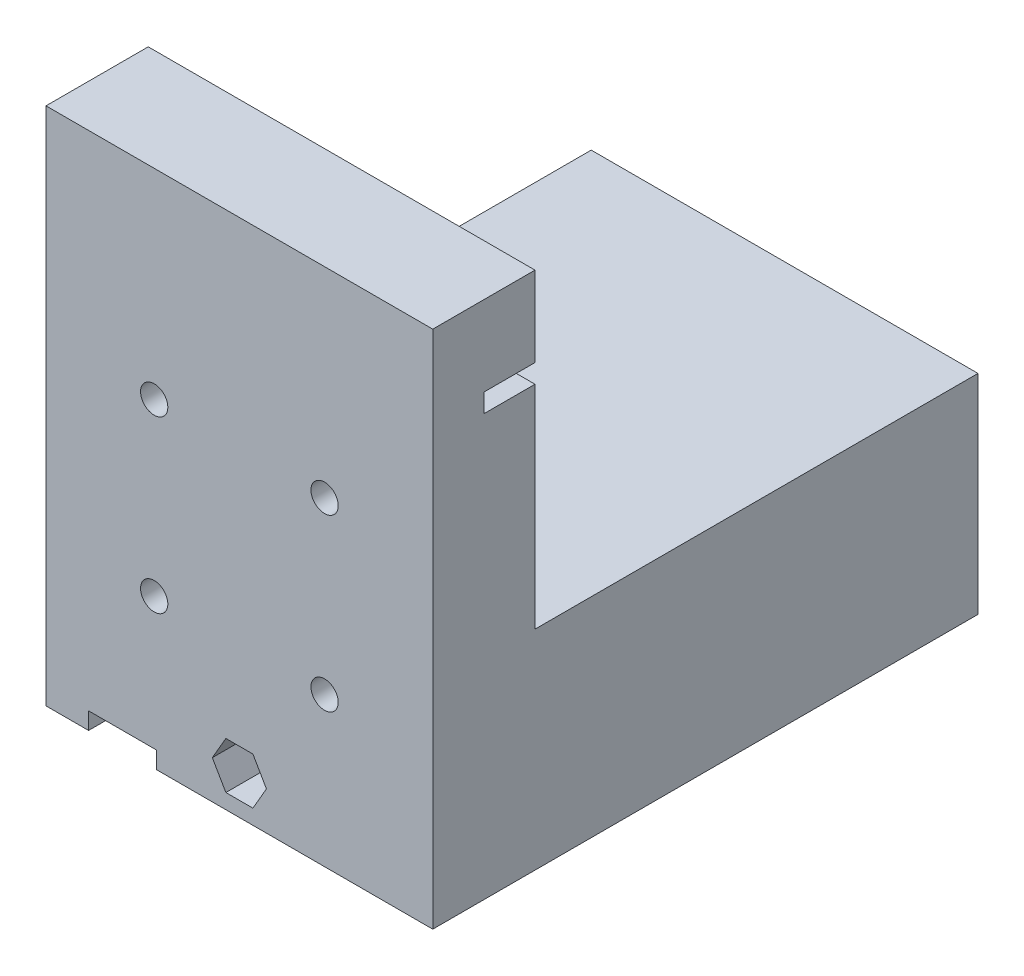
SolidWorks part; units mm, degrees
ref_plane "前视基准面" through (0, 0, 0) normal (0, 0, 1) x (1, 0, 0)
ref_plane "上视基准面" through (0, 0, 0) normal (0, 1, 0) x (1, 0, 0)
ref_plane "右视基准面" through (0, 0, 0) normal (1, 0, 0) x (0, 0, -1)
sketch "草图1" plane through (0, 0, 0) normal (0, 0, 1) x (1, 0, 0)
  line L1 (-54.7963, 27.5425) -> (-9.3963, 27.5425)
  line L2 (-54.7963, 27.5425) -> (-54.7963, 0.5425)
  line L3 (-54.7963, 0.5425) -> (-9.3963, 0.5425)
  line L4 (-9.3963, 27.5425) -> (-9.3963, 0.5425)
  dimension "D1" = 45.4
  dimension "D2" = 27
extrude "凸台-拉伸1" add sketch "草图1" along normal blind 7
sketch "草图2" plane through (0, 0, 0) normal (0, 0, -1) x (-1, 0, 0)
  line L0 (32.0963, 27.5425) -> (32.0963, 0.5425) construction
  line L1 (9.3963, 27.5425) -> (54.7963, 27.5425) construction
  line L2 (54.7963, 0.5425) -> (9.3963, 0.5425) construction
  line L3 (9.3963, 14.0425) -> (54.7963, 14.0425) construction
  line L4 (9.3963, 0.5425) -> (9.3963, 27.5425) construction
  line L5 (54.7963, 27.5425) -> (54.7963, 0.5425) construction
  circle A0 centre (22.0963, 24.0425) radius 1.6
  circle A1 centre (42.0963, 24.0425) radius 1.6
  circle A2 centre (42.0963, 4.0425) radius 1.6
  circle A3 centre (22.0963, 4.0425) radius 1.6
  point P9 (32.0963, 14.0425)
  dimension "D1" = 3.2
  dimension "D2" = 10
  dimension "D3" = 10
extrude "切除-拉伸1" cut sketch "草图2" against normal through all
sketch "草图4" plane through (0, 0, 0) normal (0, 0, -1) x (-1, 0, 0)
  line L0 (38.3463, 0.5425) -> (54.7963, 0.5425)
  line L1 (25.8463, 0.5425) -> (38.3463, 0.5425)
  line L8 (32.0963, 27.5425) -> (32.0963, 0.5425) construction
  line L9 (9.3963, 14.0425) -> (54.7963, 14.0425) construction
  line L11 (9.3963, 27.5425) -> (54.7963, 27.5425)
  line L12 (9.3963, 27.5425) -> (9.3963, 0.5425)
  line L13 (9.3963, 0.5425) -> (25.8463, 0.5425)
  line L14 (54.7963, 27.5425) -> (54.7963, 0.5425)
  circle A8 centre (42.0963, 24.0425) radius 3.1
  circle A9 centre (22.0963, 24.0425) radius 3.1
  circle A10 centre (22.0963, 24.0425) radius 3.1
  circle A11 centre (42.0963, 4.0425) radius 3.1
  circle A12 centre (22.0963, 4.0425) radius 3.1
  dimension "D1" = 1.5
extrude "凸台-拉伸2" add sketch "草图4" along normal blind 5
sketch "草图5" plane through (0, 27.5425, 0) normal (0, 1, 0) x (1, 0, 0)
  line L1 (-54.7963, 5) -> (-9.3963, 5)
  line L2 (-54.7963, 5) -> (-54.7963, -7)
  line L3 (-54.7963, -7) -> (-9.3963, -7)
  line L4 (-9.3963, 5) -> (-9.3963, -7)
extrude "凸台-拉伸3" add sketch "草图5" along normal blind 20 contours L2 L3 L4 L1
sketch "草图7" plane through (0, 0, -5) normal (0, 0, -1) x (-1, 0, 0)
  line L0 (9.3963, 27.5425) -> (54.7963, 27.5425) construction
  line L1 (9.3963, 47.5425) -> (9.3963, 0.5425) construction
  line L2 (54.7963, 0.5425) -> (54.7963, 47.5425) construction
  line L3 (9.3963, 0.5425) -> (54.7963, 0.5425) construction
  line L4 (9.3963, 37.0425) -> (54.7963, 37.0425) construction
  line L5 (32.0963, 47.5425) -> (32.0963, 27.5425) construction
  line L6 (54.7963, 47.5425) -> (9.3963, 47.5425) construction
  line L7 (9.3963, 38.1425) -> (16.3755, 38.1425)
  line L8 (9.3963, 35.9425) -> (16.3755, 35.9425)
  line L9 (9.3963, 38.1425) -> (9.3963, 35.9425)
  line L10 (54.7963, 35.9425) -> (47.8172, 35.9425)
  line L11 (54.7963, 38.1425) -> (47.8172, 38.1425)
  line L12 (54.7963, 38.1425) -> (54.7963, 35.9425)
  circle A0 centre (25.4963, 37.0425) radius 5
  circle A1 centre (38.6963, 37.0425) radius 5
  arc A2 (31.2713, 40.9984) -> (19.1117, 39.9125) centre (25.4963, 37.0425) ccw
  arc A3 (32.9213, 40.9984) -> (45.0809, 39.9125) centre (38.6963, 37.0425) cw
  arc A4 (19.1117, 34.1725) -> (31.2713, 33.0866) centre (25.4963, 37.0425) ccw
  circle A5 centre (38.6963, 37.0425) radius 7 construction
  circle A6 centre (25.4963, 37.0425) radius 7 construction
  arc A7 (45.0809, 34.1725) -> (32.9213, 33.0866) centre (38.6963, 37.0425) cw
  arc A8 (47.8172, 35.9425) -> (45.0809, 34.1725) centre (47.8172, 32.9425) ccw
  arc A9 (47.8172, 38.1425) -> (45.0809, 39.9125) centre (47.8172, 41.1425) cw
  arc A10 (16.3755, 35.9425) -> (19.1117, 34.1725) centre (16.3755, 32.9425) cw
  arc A11 (16.3755, 38.1425) -> (19.1117, 39.9125) centre (16.3755, 41.1425) ccw
  arc A12 (32.9213, 33.0866) -> (31.2713, 33.0866) centre (32.0963, 32.5215) ccw
  arc A13 (32.9213, 40.9984) -> (31.2713, 40.9984) centre (32.0963, 41.5636) cw
  point P22 (45.6963, 37.0425)
  point P25 (32.4963, 37.0425)
  point P36 (45.6094, 35.9425)
  point P39 (45.6094, 38.1425)
  point P42 (18.5833, 35.9425)
  point P45 (18.5833, 38.1425)
  point P48 (32.0963, 34.7101)
  point P51 (32.0963, 39.3749)
  dimension "D3" = 10
  dimension "D4" = 6.6
  dimension "D7" = 3
  dimension "D8" = 1
  dimension "D1" = 27
  dimension "D2" = 9.5
  dimension "D6" = 1.1
  dimension "D5" = 2
extrude "切除-拉伸3" cut sketch "草图7" against normal blind 6
sketch "草图8" plane through (0, 0.5425, 0) normal (0, -1, 0) x (1, 0, 0)
  line L1 (-54.7963, 7) -> (-9.3963, 7)
  line L2 (-54.7963, 7) -> (-54.7963, -5)
  line L3 (-54.7963, -5) -> (-38.3463, -5)
  line L4 (-9.3963, 7) -> (-9.3963, -5)
  line L7 (-25.8463, -5) -> (-9.3963, -5)
  line L8 (-38.3463, -5) -> (-25.8463, -5)
extrude "凸台-拉伸4" add sketch "草图8" along normal blind 14
sketch "草图10" plane through (0, -13.4575, 0) normal (0, -1, 0) x (1, 0, 0)
  line L0 (-9.3963, 7) -> (-54.7963, 7) construction
  line L1 (-49.7963, 7) -> (-41.7963, 7)
  line L2 (-49.7963, 7) -> (-49.7963, -5)
  line L3 (-49.7963, -5) -> (-41.7963, -5)
  line L4 (-41.7963, 7) -> (-41.7963, -5)
  line L5 (-54.7963, 7) -> (-54.7963, -5) construction
  dimension "D1" = 5
  dimension "D2" = 12
  dimension "D3" = 8
extrude "切除-拉伸6" cut sketch "草图10" against normal blind 2
sketch "草图12" plane through (0, -11.4575, 0) normal (0, -1, 0) x (1, 0, 0)
  circle A0 centre (-45.7963, 1) radius 2.2
  dimension "D1" = 4.4
extrude "切除-拉伸8" cut sketch "草图12" against normal blind 6
sketch "草图13" plane through (0, 0, -5) normal (0, 0, -1) x (-1, 0, 0)
  line L0 (22.0963, 24.0425) -> (22.0963, 4.0425) construction
  circle A0 centre (32.0963, 14.0425) radius 2.2
  dimension "D1" = 4.4
extrude "切除-拉伸9" cut sketch "草图13" against normal blind 6
sketch "草图14" plane through (0, 0, -5) normal (0, 0, -1) x (-1, 0, 0)
  line L0 (9.3963, 35.9425) -> (9.3963, -13.4575) construction
  line L1 (9.3963, 11.0425) -> (54.7963, 11.0425)
  line L2 (9.3963, 11.0425) -> (9.3963, -13.4575)
  line L3 (9.3963, -13.4575) -> (54.7963, -13.4575)
  line L4 (54.7963, 11.0425) -> (54.7963, -13.4575)
  circle A0 centre (32.0963, 14.0425) radius 2.2 construction
  circle A1 centre (22.0963, 4.0425) radius 3.1
  circle A2 centre (42.0963, 4.0425) radius 3.1
  dimension "D1" = 3
extrude "凸台-拉伸5" add sketch "草图14" along normal blind 52
sketch "草图15" plane through (0, 0, -57) normal (0, 0, -1) x (-1, 0, 0)
  line L0 (9.3963, -13.4575) -> (54.7963, -13.4575) construction
  line L1 (38.3463, -31.4575) -> (25.8463, -31.4575)
  line L2 (38.3463, -31.4575) -> (38.3463, 4.5425)
  line L3 (38.3463, 4.5425) -> (25.8463, 4.5425)
  line L4 (25.8463, -31.4575) -> (25.8463, 4.5425)
  line L5 (38.3463, -31.4575) -> (25.8463, 4.5425) construction
  line L6 (38.3463, 4.5425) -> (25.8463, -31.4575) construction
  point P0 (32.0963, -13.4575)
  point P7 (25.8463, -13.4575)
  dimension "D1" = 18
  dimension "D2" = 12.5
extrude "切除-拉伸10" cut sketch "草图15" against normal blind 5 contours L1 L4 L3 L2
sketch "草图9" plane through (0, 0, 7) normal (0, 0, 1) x (1, 0, 0)
  line L0 (-54.7963, 0.5425) -> (-9.3963, 0.5425) construction
  circle A0 centre (-32.0963, -8.9575) radius 1.6
  dimension "D1" = 3.2
  dimension "D2" = 9.5
extrude "切除-拉伸4" cut sketch "草图9" against normal through all contours A0
sketch "草图3" plane through (0, 0, 7) normal (0, 0, 1) x (1, 0, 0)
  line L1 (-28.9209, -8.9575) -> (-30.5086, -6.2075)
  line L2 (-30.5086, -6.2075) -> (-33.684, -6.2075)
  line L3 (-33.684, -6.2075) -> (-35.2717, -8.9575)
  line L4 (-35.2717, -8.9575) -> (-33.684, -11.7075)
  line L5 (-33.684, -11.7075) -> (-30.5086, -11.7075)
  line L6 (-30.5086, -11.7075) -> (-28.9209, -8.9575)
  circle A0 centre (-32.0963, -8.9575) radius 2.75 construction
  dimension "D1" = 5.5
extrude "切除-拉伸5" cut sketch "草图3" against normal blind 54.5 contours L2 L3 L4 L5 L6 L1
sketch "草图16" plane through (0, 0, -57) normal (0, 0, -1) x (-1, 0, 0)
  line L0 (54.7963, 11.0425) -> (9.3963, 11.0425) construction
  circle A0 centre (32.0963, 8.0425) radius 2.2
  circle A3 centre (32.0963, -8.9575) radius 1.6 construction
  point P6 (32.0963, 4.0425)
  dimension "D1" = 4.4
  dimension "D2" = 3
  dimension "D3" = 0
extrude "切除-拉伸11" cut sketch "草图16" against normal blind 6 contours A0
